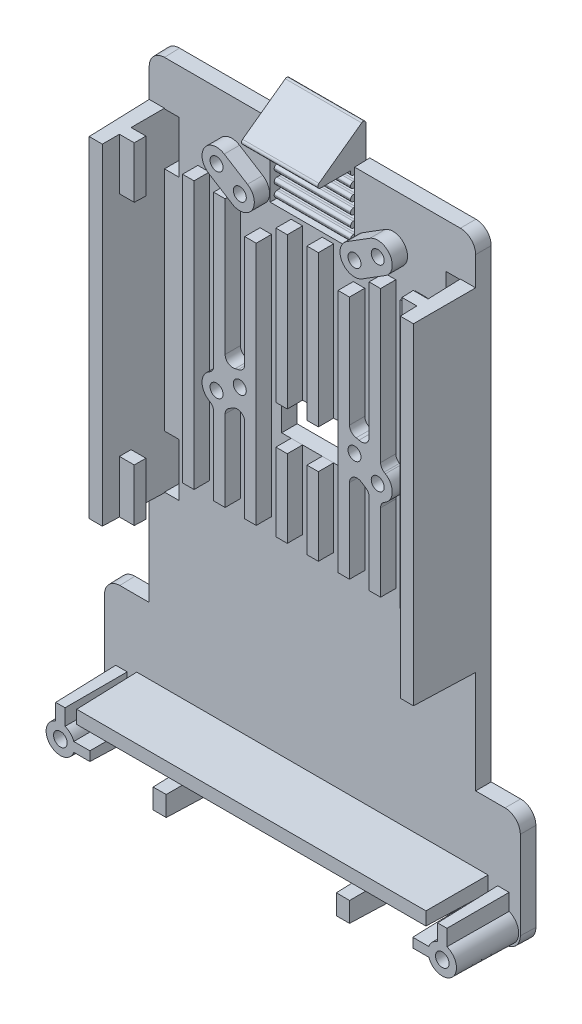
SolidWorks part; units mm, degrees
ref_plane "前视基准面" through (0, 0, 0) normal (0, 0, 1) x (1, 0, 0)
ref_plane "上视基准面" through (0, 0, 0) normal (0, 1, 0) x (1, 0, 0)
ref_plane "右视基准面" through (0, 0, 0) normal (1, 0, 0) x (0, 0, -1)
sketch "草图1" plane through (0, 0, 0) normal (0, 0, 1) x (1, 0, 0)
  line L0 (27.25, -45.8719) -> (2, -47.1952)
  line L1 (-21.4, 32.4) -> (-5.5, 32.4)
  line L2 (-21.4, 32.4) -> (-21.4, -30.4)
  line L3 (0, -30.4) -> (21.4, -30.4) construction
  line L4 (21.4, 32.4) -> (21.4, -30.4)
  line L5 (-27.25, -30.4) -> (-21.4, -30.4)
  line L6 (-27.25, -30.4) -> (-27.25, -45.8719)
  line L7 (-3.8162, -47.1) -> (0, -47.1) construction
  line L8 (27.25, -30.4) -> (27.25, -45.8719)
  line L9 (0, -47.3) -> (-3.8162, -47.1) construction
  line L10 (0, 0) -> (0, -47.3) construction
  line L11 (-21.4, -30.4) -> (0, -30.4) construction
  line L12 (-21.4, -30.4) -> (0, -30.4) construction
  line L13 (21.4, -30.4) -> (27.25, -30.4)
  line L14 (0, -30.4) -> (21.4, -30.4) construction
  line L15 (-27.25, -45.8719) -> (-27.25, -47.1) construction
  line L16 (-27.25, -47.1) -> (-3.8162, -47.1) construction
  line L17 (3.8162, -47.1) -> (27.25, -47.1) construction
  line L18 (27.25, -45.8719) -> (27.25, -47.1) construction
  line L19 (0, -47.1) -> (3.8162, -47.1) construction
  line L20 (-10, -47.1) -> (-10, -48.3) construction
  line L21 (-10, -42.3) -> (2, -42.3)
  line L22 (-10, -42.3) -> (-10, -46.7759)
  line L23 (-10, -48.3) -> (2, -48.3) construction
  line L24 (2, -42.3) -> (2, -47.1952)
  line L25 (-3.8162, -47.1) -> (-10, -46.7759) construction
  line L26 (-10, -46.7759) -> (-27.25, -45.8719)
  line L27 (2, -47.1952) -> (0, -47.3) construction
  line L28 (2, -47.1952) -> (2, -48.3) construction
  line L29 (-10, -46.7759) -> (-10, -47.1) construction
  line L30 (-5.5, 32.4) -> (5.5, 32.4) construction
  line L31 (-4, 2.5) -> (4, 2.5)
  line L32 (-4, 2.5) -> (-4, -2.5)
  line L33 (-4, -2.5) -> (4, -2.5)
  line L34 (4, 2.5) -> (4, -2.5)
  line L35 (-4, 2.5) -> (4, -2.5) construction
  line L36 (-4, -2.5) -> (4, 2.5) construction
  line L37 (-5.5, 32.4) -> (5.5, 32.4) construction
  line L38 (-5.5, 32.4) -> (-5.5, 22.9)
  line L39 (-5.5, 22.9) -> (5.5, 22.9)
  line L40 (5.5, 32.4) -> (5.5, 22.9)
  line L41 (5.5, 32.4) -> (21.4, 32.4)
  point P11 (0, 0)
  point P33 (0, 22.9)
  dimension "D1" = 174
  dimension "D2" = 47.3
  dimension "D3" = 54.5
  dimension "D4" = 16.7
  dimension "D5" = 30.4
  dimension "D6" = 42.8
  dimension "D7" = 62.8
  dimension "D8" = 2
  dimension "D9" = 10
  dimension "D10" = 42.3
  dimension "D11" = 6
  dimension "D12" = 8
  dimension "D13" = 5
  dimension "D14" = 11
  dimension "D15" = 9.5
extrude "凸台-拉伸1" add sketch "草图1" along normal blind 2 draft 1
sketch "草图2" plane through (0, 0, 2) normal (0, 0, 1) x (1, 0, 0)
  line L0 (-10.93, 22.3) -> (-10.93, -12.7)
  line L1 (-15, 22.3) -> (-13.5, 22.3)
  line L2 (-15, 22.3) -> (-15, -12.7)
  line L3 (-15, -12.7) -> (-13.5, -12.7)
  line L4 (-13.5, 22.3) -> (-13.5, -12.7)
  line L5 (-10.93, 22.3) -> (-9.43, 22.3)
  line L6 (-9.43, 22.3) -> (-9.43, -12.7)
  line L7 (-10.93, -12.7) -> (-9.43, -12.7)
  line L8 (-6.86, 22.3) -> (-6.86, -12.7)
  line L9 (-6.86, 22.3) -> (-5.36, 22.3)
  line L10 (-5.36, 22.3) -> (-5.36, -12.7)
  line L11 (-6.86, -12.7) -> (-5.36, -12.7)
  line L12 (-2.79, 22.3) -> (-2.79, -12.7)
  line L13 (-2.79, 22.3) -> (-1.29, 22.3)
  line L14 (-1.29, 22.3) -> (-1.29, -12.7)
  line L15 (-2.79, -12.7) -> (-1.29, -12.7)
  line L16 (1.28, 22.3) -> (1.28, -12.7)
  line L17 (1.28, 22.3) -> (2.78, 22.3)
  line L18 (2.78, 22.3) -> (2.78, -12.7)
  line L19 (1.28, -12.7) -> (2.78, -12.7)
  line L20 (5.35, 22.3) -> (5.35, -12.7)
  line L21 (5.35, 22.3) -> (6.85, 22.3)
  line L22 (6.85, 22.3) -> (6.85, -12.7)
  line L23 (5.35, -12.7) -> (6.85, -12.7)
  line L24 (9.42, 22.3) -> (9.42, -12.7)
  line L25 (9.42, 22.3) -> (10.92, 22.3)
  line L26 (10.92, 22.3) -> (10.92, -12.7)
  line L27 (9.42, -12.7) -> (10.92, -12.7)
  line L28 (13.49, 22.3) -> (13.49, -12.7)
  line L29 (13.49, 22.3) -> (14.99, 22.3)
  line L30 (14.99, 22.3) -> (14.99, -12.7)
  line L31 (13.49, -12.7) -> (14.99, -12.7)
  line L32 (-6.86, 19.3) -> (-5.36, 19.3)
  line L33 (5.35, 19.3) -> (6.85, 19.3)
  point P4 (0, 0)
  line M21 (-4.0349, 2.5349) -> (4.0349, 2.5349)
  line M23 (4.0349, -2.5349) -> (-4.0349, -2.5349)
  dimension "D1" = 12.7
  dimension "D2" = 22.3
  dimension "D3" = 13.5
  dimension "D4" = 1.5
  dimension "D6" = 4.07
  dimension "D7" = 3
  dimension "D5" = 8
extrude "凸台-拉伸2" add sketch "草图2" along normal blind 2 contours L4 L1 L2 L3 | L0 L7 L6 L5 | L14 L13 L12 M21 | L18 L17 L16 M21 | L12 L15 L14 M23 | L16 L19 L18 M23 | L24 L27 L26 L25 | L28 L31 L30 L29 | L32 L8 L11 L10 | L33 L20 L23 L22
sketch "草图3" plane through (0, 0, 2) normal (0, 0, 1) x (1, 0, 0)
  line L0 (0, -39.15) -> (0, 0) construction
  line L1 (-23, -39.15) -> (23, -39.15)
  line L2 (-23, -39.15) -> (-23, -41.15)
  line L3 (-23, -41.15) -> (23, -41.15)
  line L4 (23, -39.15) -> (23, -41.15)
  line L5 (-13, -42.9724) -> (-13, -45.85)
  line L6 (-13, -45.85) -> (-11, -45.85)
  line L7 (-11, -45.85) -> (-11, -42.95)
  line L8 (-11, -42.95) -> (-13, -42.9724)
  line L9 (11, -42.95) -> (13, -42.9724)
  line L10 (11, -45.85) -> (11, -42.95)
  line L11 (13, -45.85) -> (11, -45.85)
  line L12 (13, -42.9724) -> (13, -45.85)
  line L13 (23.146, -43) -> (23.146, -44.5)
  line L14 (-25.75, -39.746) -> (-24.25, -39.746)
  line L15 (-25.75, -39.746) -> (-25.75, -41.896)
  line L16 (-25.75, -41.896) -> (-24.25, -41.896)
  line L17 (-24.25, -39.746) -> (-24.25, -41.896)
  line L18 (-20.996, -43) -> (-23.146, -43)
  line L19 (-20.996, -43) -> (-20.996, -44.5)
  line L20 (-20.996, -44.5) -> (-23.146, -44.5)
  line L22 (20.996, -44.5) -> (23.146, -44.5)
  line L23 (20.996, -43) -> (20.996, -44.5)
  line L24 (20.996, -43) -> (23.146, -43)
  line L25 (24.25, -39.746) -> (24.25, -41.896)
  line L26 (25.75, -41.896) -> (24.25, -41.896)
  line L27 (25.75, -39.746) -> (25.75, -41.896)
  line L28 (25.75, -39.746) -> (24.25, -39.746)
  line L29 (23, -39.15) -> (23, -41.15)
  line L32 (-23.146, -43) -> (-23.146, -44.5)
  arc A0 (-23.146, -43) -> (-23.146, -44.5) centre (-25, -43.75) ccw
  circle A1 centre (-25, -43.75) radius 0.75
  circle A2 centre (25, -43.75) radius 0.75
  circle A3 centre (25, -43.75) radius 2
  point P0 (0, 0)
  point P29 (0, 0)
  dimension "D9" = 25
  dimension "D10" = 43.75
  dimension "D11" = 1.5
  dimension "D12" = 4
  dimension "D1" = 39.15
  dimension "D2" = 2
  dimension "D3" = 46
  dimension "D4" = 11
  dimension "D5" = 13
  dimension "D6" = 89.358
  dimension "D7" = 2.9
  dimension "D8" = 45.85
  dimension "D13" = 1.5
  dimension "D14" = 1.5
  dimension "D15" = 2.15
extrude "凸台-拉伸3" add sketch "草图3" along normal blind 8 draft 1
sketch "草图4" plane through (0, 0, 2) normal (0, 0, 1) x (1, 0, 0)
  line L0 (-21.3651, 32.3651) -> (-21.3651, -30.4349) construction
  line L1 (-21.3651, 26.6) -> (-19.3651, 26.6)
  line L2 (-21.3651, 26.6) -> (-21.3651, -17)
  line L3 (-21.3651, -17) -> (-19.3651, -17)
  line L4 (-19.3651, 26.6) -> (-19.3651, -17)
  line L5 (0, 0) -> (0, 38.1057) construction
  line L6 (19.3651, 26.6) -> (19.3651, -17)
  line L7 (21.3651, -17) -> (19.3651, -17)
  line L8 (21.3651, 26.6) -> (21.3651, -17)
  line L9 (21.3651, 26.6) -> (19.3651, 26.6)
  point P6 (0, 0)
  dimension "D1" = 26.6
  dimension "D2" = 43.6
  dimension "D3" = 2
extrude "凸台-拉伸4" add sketch "草图4" along normal blind 8 draft 1
ref_plane "基准面1" through (0, 0, 6.3) normal (0, 0, 1) x (1, 0, 0)
sketch "草图5" plane through (0, 0, 6.3) normal (0, 0, 1) x (1, 0, 0)
  line L0 (0, 0) -> (0, 38.0664) construction
  line L1 (-17.5, 26.5249) -> (-20.1, 26.5249)
  line L2 (-17.5, 26.5249) -> (-17.5, 19.7249)
  line L3 (-17.5, 19.7249) -> (-20.1, 19.7249)
  line L4 (-20.1, 26.5249) -> (-20.1, 19.7249)
  line L5 (-17.5, -10) -> (-20.1, -10)
  line L6 (-17.5, -10) -> (-17.5, -16.9249)
  line L7 (-17.5, -16.9249) -> (-20.1, -16.9249)
  line L8 (-20.1, -10) -> (-20.1, -16.9249)
  point P4 (0, 0)
  point P16 (-19.4401, -16.9249)
  point P17 (-19.4401, 26.5249)
  dimension "D1" = 17.5
  dimension "D3" = 6.8
  dimension "D4" = 10
  dimension "D6" = 2.6
extrude "凸台-拉伸5" add sketch "草图5" along normal blind 1.5 draft 1
mirror "镜向1" about plane through (0, 0, 0) normal (1, 0, 0) of "凸台-拉伸5"
sketch "草图6" plane through (0, 0, 2) normal (0, 0, 1) x (1, 0, 0)
  line L1 (-19.4401, 26.5249) -> (-17.5, 26.5249) construction
  line L2 (-17.5, 26.5249) -> (-17.5, 19.7249) construction
  line L3 (-17.5, 19.7249) -> (-19.4401, 19.7249) construction
  line L5 (19.4401, 19.7249) -> (17.5, 19.7249) construction
  line L6 (17.5, 19.7249) -> (17.5, 26.5249) construction
  line L7 (17.5, 26.5249) -> (19.4401, 26.5249) construction
  line L8 (-19.3651, 19.7249) -> (-19.3651, 26.5249)
  line L9 (-19.3651, 26.5249) -> (-17.5, 26.5249)
  line L10 (-17.5, 26.5249) -> (-17.5, 19.7249)
  line L11 (-17.5, 19.7249) -> (-19.3651, 19.7249)
  line L12 (19.3651, 26.5249) -> (19.3651, 19.7249)
  line L13 (19.3651, 19.7249) -> (17.5, 19.7249)
  line L14 (17.5, 19.7249) -> (17.5, 26.5249)
  line L15 (17.5, 26.5249) -> (19.3651, 26.5249)
  line L17 (19.4401, -16.9249) -> (17.5, -16.9249) construction
  line L18 (17.5, -16.9249) -> (17.5, -10) construction
  line L19 (17.5, -10) -> (19.4401, -10) construction
  line L21 (-19.4401, -10) -> (-17.5, -10) construction
  line L22 (-17.5, -10) -> (-17.5, -16.9249) construction
  line L23 (-17.5, -16.9249) -> (-19.4401, -16.9249) construction
  line L24 (19.3651, -10) -> (19.3651, -16.9249)
  line L25 (19.3651, -16.9249) -> (17.5, -16.9249)
  line L26 (17.5, -16.9249) -> (17.5, -10)
  line L27 (17.5, -10) -> (19.3651, -10)
  line L28 (-19.3651, -16.9249) -> (-19.3651, -10)
  line L29 (-19.3651, -10) -> (-17.5, -10)
  line L30 (-17.5, -10) -> (-17.5, -16.9249)
  line L31 (-17.5, -16.9249) -> (-19.3651, -16.9249)
  line L32 (-19.3651, -17) -> (-19.3651, 26.6) construction
  line L33 (19.3651, 26.6) -> (19.3651, -17) construction
extrude "切除-拉伸1" cut sketch "草图6" against normal through all draft 1
sketch "草图7" plane through (0, 0, 2) normal (0, 0, 1) x (1, 0, 0)
  line L0 (-8.5162, 3.5113) -> (-11.5568, 1.6113)
  line L1 (-7.5094, 1.9) -> (-10.55, 0) construction
  line L2 (-6.5025, 0.2887) -> (-9.5432, -1.6113)
  line L3 (0, 0) -> (0, 1.3391) construction
  line L4 (-10.55, 25.7) -> (-7.5094, 23.8) construction
  line L5 (-11.5568, 24.0887) -> (-8.5162, 22.1887)
  line L6 (-9.5432, 27.3113) -> (-6.5025, 25.4113)
  arc A0 (-9.3632, 24.2162) -> (-8.9387, 24.6932) centre (-10.55, 25.7) ccw construction
  arc A1 (-8.5162, 22.1887) -> (-6.5025, 25.4113) centre (-7.5094, 23.8) ccw
  arc A2 (-11.5568, 1.6113) -> (-9.5432, -1.6113) centre (-10.55, 0) ccw
  arc A3 (-6.5025, 0.2887) -> (-8.5162, 3.5113) centre (-7.5094, 1.9) ccw
  arc A4 (-8.5162, 3.5113) -> (-9.3632, 1.4838) centre (-7.5094, 1.9) ccw construction
  arc A5 (-9.3632, 1.4838) -> (-11.5568, 1.6113) centre (-10.55, 0) ccw construction
  arc A6 (-9.3632, 1.4838) -> (-9.1207, 0.8932) centre (-7.5094, 1.9) ccw construction
  arc A7 (-8.9387, 1.0068) -> (-9.3632, 1.4838) centre (-10.55, 0) ccw construction
  arc A8 (-8.6962, 0.4162) -> (-8.9387, 1.0068) centre (-10.55, 0) ccw construction
  arc A9 (-9.1207, 0.8932) -> (-8.6962, 0.4162) centre (-7.5094, 1.9) ccw construction
  arc A10 (-9.5432, -1.6113) -> (-8.6962, 0.4162) centre (-10.55, 0) ccw construction
  arc A11 (-8.6962, 0.4162) -> (-6.5025, 0.2887) centre (-7.5094, 1.9) ccw construction
  arc A12 (-11.5568, 24.0887) -> (-9.3632, 24.2162) centre (-10.55, 25.7) ccw construction
  arc A13 (-9.3632, 24.2162) -> (-8.5162, 22.1887) centre (-7.5094, 23.8) ccw construction
  arc A14 (-6.5025, 25.4113) -> (-8.6962, 25.2838) centre (-7.5094, 23.8) ccw construction
  arc A15 (-9.1207, 24.8068) -> (-9.3632, 24.2162) centre (-7.5094, 23.8) ccw construction
  arc A16 (-8.6962, 25.2838) -> (-9.5432, 27.3113) centre (-10.55, 25.7) ccw construction
  arc A17 (-9.5432, 27.3113) -> (-11.5568, 24.0887) centre (-10.55, 25.7) ccw
  arc A18 (-8.6962, 25.2838) -> (-9.1207, 24.8068) centre (-7.5094, 23.8) ccw construction
  arc A19 (-8.9387, 24.6932) -> (-8.6962, 25.2838) centre (-10.55, 25.7) ccw construction
  circle A20 centre (-10.55, 25.7) radius 0.85
  circle A21 centre (-7.5094, 23.8) radius 0.85
  circle A22 centre (-10.55, 0) radius 0.85
  circle A23 centre (-7.5094, 1.9) radius 0.85
  point P17 (0, 0)
  dimension "D4" = 1.9
  dimension "D5" = 21.9
  dimension "D6" = 1.7
  dimension "D1" = 1.9
  dimension "D2" = 10.55
  dimension "D3" = 58
extrude "凸台-拉伸6" add sketch "草图7" along normal blind 2
sketch "草图8" plane through (0, 0, 4) normal (0, 0, 1) x (1, 0, 0)
  line L2 (-8.5162, 3.5113) -> (-11.5568, 1.6113)
  line L3 (-9.5432, -1.6113) -> (-6.5025, 0.2887)
  line L4 (-8.5162, 3.5113) -> (-11.5568, 1.6113)
  line L5 (-9.5432, -1.6113) -> (-6.5025, 0.2887)
  line L6 (-11.5568, 24.0887) -> (-8.5162, 22.1887)
  line L7 (-6.5025, 25.4113) -> (-9.5432, 27.3113)
  line L8 (-11.5568, 24.0887) -> (-8.5162, 22.1887)
  line L9 (-6.5025, 25.4113) -> (-9.5432, 27.3113)
  circle A1 centre (-7.5094, 1.9) radius 0.85
  arc A2 (-11.5568, 1.6113) -> (-9.5432, -1.6113) centre (-10.55, 0) ccw
  arc A3 (-6.5025, 0.2887) -> (-8.5162, 3.5113) centre (-7.5094, 1.9) ccw
  arc A4 (-11.5568, 1.6113) -> (-9.5432, -1.6113) centre (-10.55, 0) ccw
  arc A5 (-6.5025, 0.2887) -> (-8.5162, 3.5113) centre (-7.5094, 1.9) ccw
  circle A6 centre (-7.5094, 1.9) radius 0.85
  circle A7 centre (-10.55, 0) radius 0.85
  circle A8 centre (-10.55, 0) radius 0.85
  circle A9 centre (-7.5094, 23.8) radius 0.85
  circle A10 centre (-7.5094, 23.8) radius 0.85
  circle A11 centre (-10.55, 25.7) radius 0.85
  circle A12 centre (-10.55, 25.7) radius 0.85
  arc A14 (-8.5162, 22.1887) -> (-6.5025, 25.4113) centre (-7.5094, 23.8) ccw
  arc A15 (-9.5432, 27.3113) -> (-11.5568, 24.0887) centre (-10.55, 25.7) ccw
  arc A16 (-8.5162, 22.1887) -> (-6.5025, 25.4113) centre (-7.5094, 23.8) ccw
  arc A17 (-9.5432, 27.3113) -> (-11.5568, 24.0887) centre (-10.55, 25.7) ccw
  line M35 (-10.93, 0.7603) -> (-10.93, -0.7603)
  line M37 (-6.86, 2.4485) -> (-6.86, 1.3515)
  dimension "D1" = 0
  dimension "D2" = 0
  dimension "D3" = 0
  dimension "D4" = 0
  dimension "D5" = 0
  dimension "D6" = 0
extrude "切除-拉伸3" cut sketch "草图8" against normal up to surface (2 mm away) contours A8 M35 | A6 M37 up to face at (-9.7, 25.7, 2)
mirror "镜向3" about plane through (0, 0, 0) normal (1, 0, 0) of "切除-拉伸3", "凸台-拉伸6"
fillet "圆角1" radius 1 12 edges at (-6.86, 3.6856, 3) (-9.43, 2.9403, 3) (-10.93, 2.003, 3) (-9.43, -1.5406, 3) (-6.86, 0.0653, 3) (-10.93, -1.8616, 3) (10.92, 2.0092, 3) (9.42, 2.9465, 3) (6.85, 3.6819, 3) (10.92, -1.8636, 3) (9.42, -1.5343, 3) (6.85, 0.0716, 3)
sketch "草图10" plane through (0, 0, 0) normal (1, 0, 0) x (0, 0, -1)
  line L0 (0, 22.8) -> (0, 36.1131)
  line L1 (-0.5557, 36.3962) -> (-6.1481, 32.3332)
  line L2 (-5.9424, 31.7) -> (-2, 31.7)
  line L3 (-2, 31.7) -> (-2, 31.375)
  line L4 (-1.35, 22.8) -> (0, 22.8)
  line L5 (0, -10.0349) -> (0, -16.89) construction
  line L6 (-1.65, 28.8) -> (-1.35, 28.8)
  line L7 (-1.65, 29.525) -> (-1.35, 29.525)
  line L8 (-1.65, 31.025) -> (-1.35, 31.025)
  line L10 (-1.65, 30.3) -> (-1.35, 30.3)
  line L11 (-1, 30.675) -> (-1, 30.65)
  line L12 (-2, 29.95) -> (-2, 29.875)
  line L13 (-1.65, 27.3) -> (-1.35, 27.3)
  line L14 (-1.65, 28.025) -> (-1.35, 28.025)
  line L15 (-2, 28.45) -> (-2, 28.375)
  line L16 (-1.65, 25.8) -> (-1.35, 25.8)
  line L17 (-1.65, 26.525) -> (-1.35, 26.525)
  line L18 (-2, 26.95) -> (-2, 26.875)
  line L19 (-1.65, 24.3) -> (-1.35, 24.3)
  line L20 (-1.65, 25.025) -> (-1.35, 25.025)
  line L21 (-2, 25.45) -> (-2, 25.375)
  line L23 (-1.65, 23.525) -> (-1.35, 23.525)
  line L24 (-2, 23.95) -> (-2, 23.875)
  line L25 (-1, 29.175) -> (-1, 29.15)
  line L26 (-1, 27.675) -> (-1, 27.65)
  line L27 (-1, 26.175) -> (-1, 26.15)
  line L28 (-1, 24.675) -> (-1, 24.65)
  line L29 (-1, 23.175) -> (-1, 23.15)
  line L32 (-1.65, 22.8) -> (-1.35, 22.8) construction
  arc A0 (-2, 31.375) -> (-1.65, 31.025) centre (-1.65, 31.375) ccw
  arc A1 (-1, 30.675) -> (-1.35, 31.025) centre (-1.35, 30.675) ccw
  arc A2 (-1.35, 30.3) -> (-1, 30.65) centre (-1.35, 30.65) ccw
  arc A3 (-2, 29.95) -> (-1.65, 30.3) centre (-1.65, 29.95) cw
  arc A4 (-2, 28.45) -> (-1.65, 28.8) centre (-1.65, 28.45) cw
  arc A5 (-1, 29.175) -> (-1.35, 29.525) centre (-1.35, 29.175) ccw
  arc A6 (-1.35, 28.8) -> (-1, 29.15) centre (-1.35, 29.15) ccw
  arc A7 (-2, 29.875) -> (-1.65, 29.525) centre (-1.65, 29.875) ccw
  arc A8 (-2, 26.95) -> (-1.65, 27.3) centre (-1.65, 26.95) cw
  arc A9 (-1, 27.675) -> (-1.35, 28.025) centre (-1.35, 27.675) ccw
  arc A10 (-1.35, 27.3) -> (-1, 27.65) centre (-1.35, 27.65) ccw
  arc A11 (-2, 28.375) -> (-1.65, 28.025) centre (-1.65, 28.375) ccw
  arc A12 (-2, 25.45) -> (-1.65, 25.8) centre (-1.65, 25.45) cw
  arc A13 (-1, 26.175) -> (-1.35, 26.525) centre (-1.35, 26.175) ccw
  arc A14 (-1.35, 25.8) -> (-1, 26.15) centre (-1.35, 26.15) ccw
  arc A15 (-2, 26.875) -> (-1.65, 26.525) centre (-1.65, 26.875) ccw
  arc A16 (-2, 23.95) -> (-1.65, 24.3) centre (-1.65, 23.95) cw
  arc A17 (-1, 24.675) -> (-1.35, 25.025) centre (-1.35, 24.675) ccw
  arc A18 (-1.35, 24.3) -> (-1, 24.65) centre (-1.35, 24.65) ccw
  arc A19 (-2, 25.375) -> (-1.65, 25.025) centre (-1.65, 25.375) ccw
  arc A21 (-1, 23.175) -> (-1.35, 23.525) centre (-1.35, 23.175) ccw
  arc A22 (-1.35, 22.8) -> (-1, 23.15) centre (-1.35, 23.15) ccw
  arc A23 (-2, 23.875) -> (-1.65, 23.525) centre (-1.65, 23.875) ccw
  arc A24 (-0.5557, 36.3962) -> (0, 36.1131) centre (-0.35, 36.1131) cw
  arc A25 (-6.1481, 32.3332) -> (-5.9424, 31.7) centre (-5.9424, 32.05) ccw
  arc A26 (-2, 22.45) -> (-1.65, 22.8) centre (-1.65, 22.45) cw construction
  point P12 (0, 0)
  point P15 (-1, 31.025)
  point P21 (-1, 30.3)
  point P90 (0, 36.8)
  point P93 (-7.0195, 31.7)
  dimension "D8" = 0.35
  dimension "D10" = 0.35
  dimension "D11" = 0.35
  dimension "D12" = 0.35
  dimension "D13" = 6
  dimension "D14" = 0.35
  dimension "D1" = 54
  dimension "D2" = 14
  dimension "D3" = 22.8
  dimension "D4" = 2
  dimension "D5" = 5.1
  dimension "D6" = 0.725
  dimension "D7" = 0.675
  dimension "D9" = 1
extrude "凸台-拉伸7" add sketch "草图10" along normal mid plane 10
fillet "圆角2" radius 2 6 edges at (-21.3825, 32.3825, 1) (-27.2325, -30.4175, 1) (-27.2325, -45.8553, 1) (27.2325, -30.4175, 1) (27.2325, -45.8553, 1) (21.3825, 32.3825, 1)
sketch "草图11" plane through (0, 0, 4) normal (0, 0, 1) x (1, 0, 0)
  circle A0 centre (10.55, 0) radius 0.85 construction
  circle A1 centre (7.5094, 1.9) radius 0.85 construction
  circle A2 centre (10.55, 25.7) radius 0.85 construction
  circle A3 centre (7.5094, 23.8) radius 0.85 construction
  circle A4 centre (-7.5094, 23.8) radius 0.85 construction
  circle A5 centre (-10.55, 25.7) radius 0.85 construction
  circle A6 centre (-10.55, 0) radius 0.85 construction
  circle A7 centre (-7.5094, 1.9) radius 0.85 construction
  circle A8 centre (10.55, 0) radius 0.85
  circle A9 centre (7.5094, 1.9) radius 0.85
  circle A10 centre (10.55, 25.7) radius 0.85
  circle A11 centre (7.5094, 23.8) radius 0.85
  circle A12 centre (-7.5094, 23.8) radius 0.85
  circle A13 centre (-10.55, 25.7) radius 0.85
  circle A14 centre (-10.55, 0) radius 0.85
  circle A15 centre (-7.5094, 1.9) radius 0.85
extrude "切除-拉伸4" cut sketch "草图11" against normal through all
